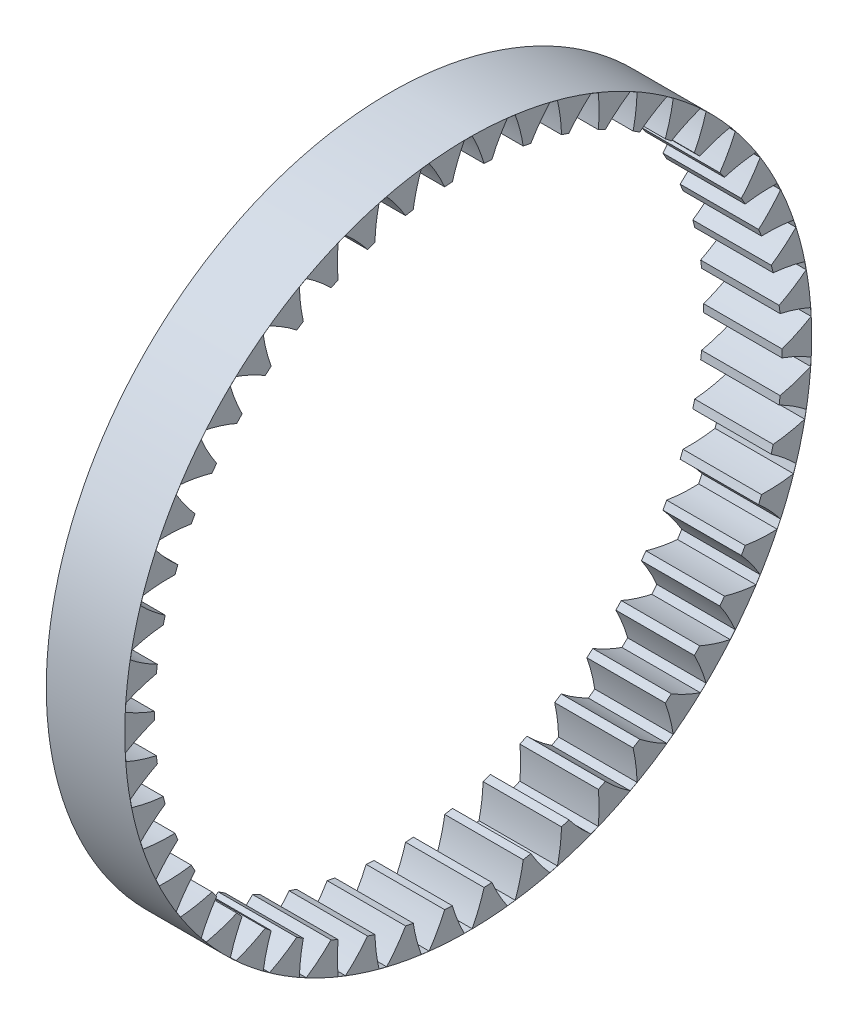
SolidWorks part; units mm, degrees
ref_plane "Plane1" through (0, 0, 0) normal (0, 0, 1) x (1, 0, 0)
ref_plane "Plane2" through (0, 0, 0) normal (0, 1, 0) x (1, 0, 0)
ref_plane "Plane3" through (0, 0, 0) normal (1, 0, 0) x (0, 0, -1)
sketch "HoldingSke" plane through (0, 0, 0) normal (0, 1, 0) x (1, 0, 0)
  line L0 (0, 0) -> (0.3214, -0.383)
  line L1 (-15, 0) -> (100, 0) construction
  line L2 (0, 0) -> (-2.1039, 2.3779)
  line L3 (0, 0) -> (-11.863, 4.5341)
  line L4 (0, 0) -> (5.5511, 6.6156)
  line L5 (0, 0) -> (-23.7986, -8.8762)
  line L6 (0, 0) -> (-10.5278, -7.1032)
  line L7 (-2.1039, 2.3779) -> (3.3635, 27.1825)
  line L8 (-76.2, 4.3779) -> (-54.61, 4.3779)
  line L9 (-71.009, 38.7566) -> (-53.1078, 45.2721)
  line L10 (-76.2, 71.12) -> (104.1128, 71.12)
  line L11 (0, 0) -> (-12, 0)
  line L12 (-76.2, 101.6) -> (-76.133, 101.6)
  line L13 (24.9733, 27.94) -> (52.9518, 28.4284)
  line L14 (24.9733, 27.94) -> (24.9743, 27.94)
  line L15 (24.9733, 27.94) -> (100.4006, 29.5858)
  circle A0 centre (0, 0) radius 12.5
  circle A1 centre (0, 0) radius 12.7
  circle A2 centre (0, 0) radius 12.7
  dimension "MHD" = 25.4
  dimension "Hub_dia" = 25.4
  dimension "Diameter" = 25
  dimension "Num_teeth" = 50
  dimension "Pitch" = 0.5
  dimension "Overall_len" = 25.4
  dimension "Show_teeth" = 50
  dimension "Thickness" = 12.7
  dimension "OAL" = 25.4001
  dimension "T_dim" = 21.59
  dimension "Ap" = 20
  dimension "H" = 19.05
  dimension "Pitch_radius" = 180.3128
  dimension "Width" = 12
  dimension "Backlash" = 0.067
  dimension "Addendum_fac" = 1
  dimension "Dedendum_fac" = 1.25
  dimension "Clearance_fac" = 0.25
  dimension "Dedendum_add" = 0.001
  dimension "Module" = 2
sketch "BasProSke" plane through (0, 0, 0) normal (0, 1, 0) x (1, 0, 0)
  line L0 (-10, 0) -> (60, 0) construction
  line L1 (0, 48) -> (0, 52.5264)
  line L2 (0, 48) -> (12, 48)
  line L3 (12, 48) -> (12, 52.5264)
  line L4 (12, 52.5264) -> (0, 52.5264)
  dimension "Thickness" = 12
  dimension "Diameter" = 105.0528
  dimension "Inside_diameter" = 96
revolve "Base-Revolve" add sketch "BasProSke" angle 360 about L0
sketch "TooCutSke" plane through (0, 0, 0) normal (1, 0, 0) x (0, 0, -1)
  line L3 (1.738, 49.9698) -> (1.738, 53.6633) construction
  line L4 (0, 0) -> (0, 59.563) construction
  line L5 (0, 0) -> (-4.2903, 68.1927) construction
  line L6 (-21.6015, 41.0107) -> (35.113, 44.5789) construction
  circle A0 centre (0, 0) radius 50 construction
  circle A1 centre (0, 0) radius 52.501 construction
  circle A2 centre (0, 0) radius 42.2862 construction
  circle A3 centre (0, 0) radius 47.9746 construction
  arc A4 (2.4267, 47.9132) -> (0.6033, 52.4975) centre (-21.6015, 41.0107) ccw
  arc A5 (2.4267, 47.9132) -> (-2.4267, 47.9132) centre (0, 0) ccw
  arc A6 (0.6033, 52.4975) -> (-0.6033, 52.4975) centre (0, 0) ccw
  arc A7 (-0.6033, 52.4975) -> (-2.4267, 47.9132) centre (21.6015, 41.0107) ccw
  dimension "Pitch_dia" = 100
  dimension "Base_dia" = 84.5723
  dimension "Root_dia" = 105.002
  dimension "Overcut_dia" = 95.9492
  dimension "Flank_rad" = 25
  dimension "Half_ang" = 3.6
  dimension "Half_CT" = 1.738
extrude "ToothCut" cut sketch "TooCutSke" along normal through all
fillet "Breaks" [suppressed] radius 0.2
fillet "RootFillets" [suppressed] radius 0.501
pattern_circular "TeethCuts" count 50 every 7.2 about axis through (-10, 0, 0) along (1, 0, 0) of "RootFillets", "Breaks", "ToothCut"
equation "' \"Module@HoldingSke\" = 6.35"
equation "' \"Num_teeth@HoldingSke\" = 24"
equation "' \"Ap@HoldingSke\" =  14.5"
equation "' \"Ap@HoldingSke\" = 14.5"
equation "' \"Width@HoldingSke\" = 12"
equation "' \"Diameter@HoldingSke\" = 8 * 25.4"
equation "' \"Show_teeth@HoldingSke\" = 100"
equation "' \"Backlash@HoldingSke\" = 0.009 * 25.4"
equation "' \"Addendum_fac@HoldingSke\" = 1.0"
equation "' \"Dedendum_fac@HoldingSke\" = 1.25"
equation "' \"Dedendum_add@HoldingSke\" = 0.00005 * 25.4"
equation "' \"Clearance_fac@HoldingSke\" = 0.25"
equation "\"Pitch@HoldingSke\" = 1 / \"Module@HoldingSke\" "
equation "\"Overcut_dia@TooCutSke\" = (\"Num_teeth@HoldingSke\" - 2 * \"Addendum_fac@HoldingSke\") / \"Pitch@HoldingSke\" - 0.002 * 25.4"
equation "\"Pitch_dia@TooCutSke\" = \"Num_teeth@HoldingSke\" / \"Pitch@HoldingSke\""
equation "\"Base_dia@TooCutSke\" = \"Num_teeth@HoldingSke\" / \"Pitch@HoldingSke\" * cos((\"Ap@HoldingSke\"  * 3.14159265 / 180)) * 0.90"
equation "\"Root_dia@TooCutSke\" = \"Num_teeth@HoldingSke\"  / \"Pitch@HoldingSke\" + 2 *  \"Dedendum_fac@HoldingSke\"/ \"Pitch@HoldingSke\" + \"Dedendum_add@HoldingSke\" * 2"
equation "\"Half_ang@TooCutSke\" = 180 / \"Num_teeth@HoldingSke\""
equation "\"Half_CT@TooCutSke\" = \"Num_teeth@HoldingSke\" / \"Pitch@HoldingSke\" * sin((3.14159265 / 2 / \"Num_teeth@HoldingSke\")) / 2 + 10 * \"Backlash@HoldingSke\" / 4"
equation "\"Flank_rad@TooCutSke\" = \"Num_teeth@HoldingSke\" / \"Pitch@HoldingSke\" / 4"
equation "\"Radius@RootFillets\"= \"Clearance_fac@HoldingSke\" / \"Pitch@HoldingSke\" + \"Dedendum_add@HoldingSke\""
equation "\"Break_rad@Breaks\" = 0.02 / \"Pitch@HoldingSke\" * 5"
equation "\"Num_teeth@TeethCuts\" = int( \"Show_teeth@HoldingSke\" ) + 1"
equation "\"Num_teeth@TeethCuts\" = ((sgn( \"Num_teeth@TeethCuts\" - \"Num_teeth@HoldingSke\" )-1)*( \"Num_teeth@TeethCuts\" - \"Num_teeth@HoldingSke\" ))/-2+ \"Num_teeth@HoldingSke\""
equation "\"Num_teeth@TeethCuts\" = ((sgn( \"Num_teeth@TeethCuts\" - 2.0)+1)*( \"Num_teeth@TeethCuts\" - 2.0))/2 +2.0"
equation "\"Angle@TeethCuts\" = 360.0 / \"Num_teeth@HoldingSke\""
equation "\"Diameter@BasProSke\" = \"Num_teeth@HoldingSke\"  / \"Pitch@HoldingSke\" + 2 *  \"Dedendum_fac@HoldingSke\"/ \"Pitch@HoldingSke\" + \"Dedendum_add@HoldingSke\" * 2 + 0.002 * 25.4"
equation "\"Diameter@BasProSke\" = ((sgn( \"Diameter@BasProSke\"  - \"Diameter@HoldingSke\" )+1)*( \"Diameter@BasProSke\"  - \"Diameter@HoldingSke\" ))/2 + \"Diameter@HoldingSke\""
equation "\"Inside_diameter@BasProSke\" =  (\"Num_teeth@HoldingSke\" - 2 * \"Addendum_fac@HoldingSke\") / \"Pitch@HoldingSke\" "
equation "\"Thickness@BasProSke\"  = \"Width@HoldingSke\""
